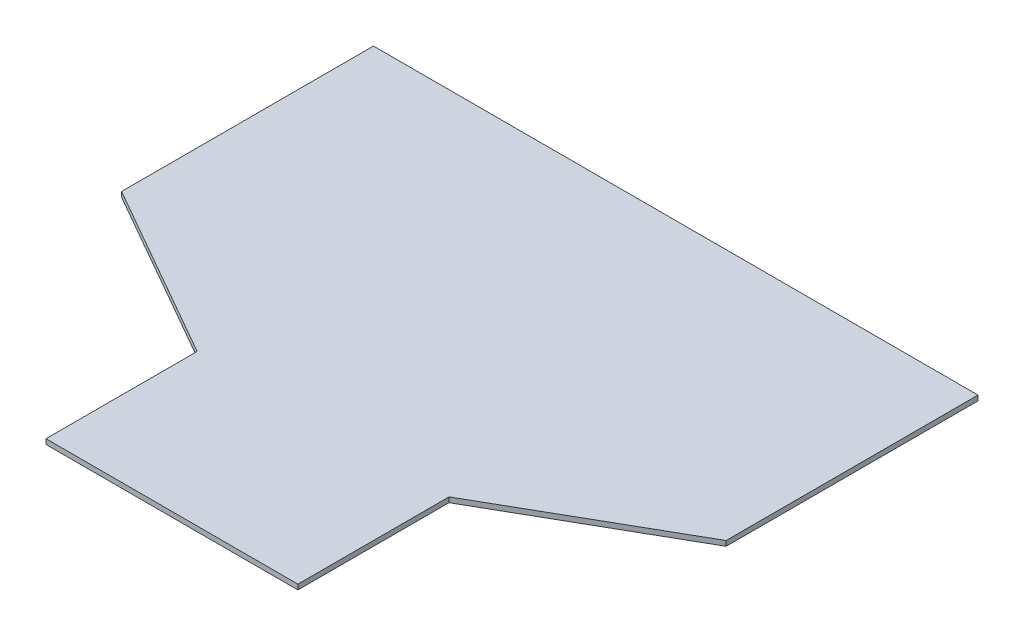
SolidWorks part; units mm, degrees
ref_plane "Front Plane" through (0, 0, 0) normal (0, 0, 1) x (1, 0, 0)
ref_plane "Top Plane" through (0, 0, 0) normal (0, 1, 0) x (1, 0, 0)
ref_plane "Right Plane" through (0, 0, 0) normal (1, 0, 0) x (0, 0, -1)
sketch "Sketch1" plane through (0, 0, 0) normal (0, 1, 0) x (1, 0, 0)
  line L0 (-152.4, 0) -> (152.4, 0)
  line L1 (-152.4, 0) -> (-152.4, -127)
  line L2 (-152.4, -127) -> (-63.5, -177.8)
  line L3 (-63.5, -177.8) -> (-63.5, -254)
  line L4 (-63.5, -254) -> (63.5, -254)
  line L5 (63.5, -254) -> (63.5, -177.8)
  line L6 (63.5, -177.8) -> (152.4, -127)
  line L7 (152.4, -127) -> (152.4, 0)
  point P4 (0, 0)
  dimension "D1" = 304.8
  dimension "D2" = 127
  dimension "D3" = 88.9
  dimension "D4" = 88.9
  dimension "D5" = 76.2
  dimension "D6" = 50.8
extrude "Boss-Extrude1" add sketch "Sketch1" along normal blind 2.54
